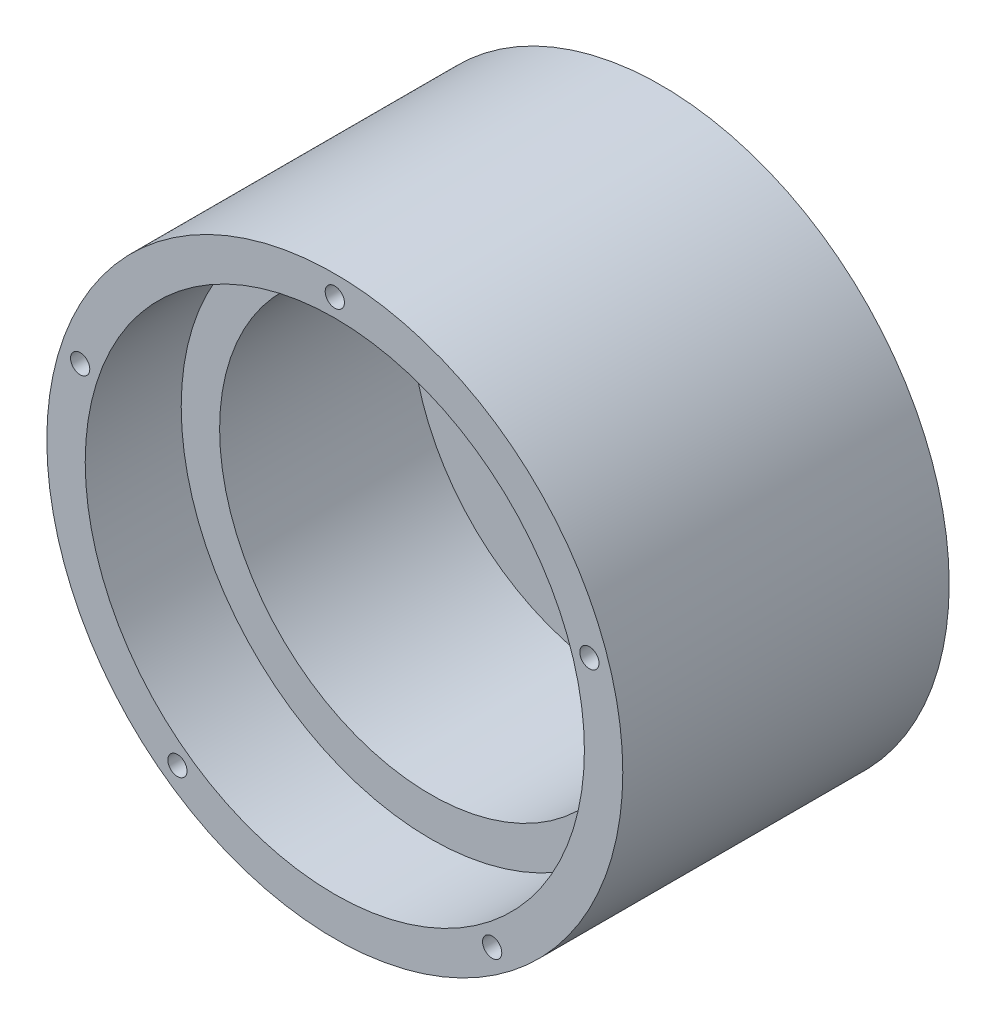
SolidWorks part; units mm, degrees
ref_plane "Front Plane" through (0, 0, 0) normal (1, 0, 0) x (0, 1, 0)
ref_plane "Top Plane" through (0, 0, 0) normal (0, 0, 1) x (0, 1, 0)
ref_plane "Right Plane" through (0, 0, 0) normal (0, 1, 0) x (-1, 0, 0)
sketch "Sketch2" plane through (0, 0, 0) normal (0, 0, 1) x (0, 1, 0)
  circle A0 centre (0, 0) radius 75
  dimension "D1" = 150
extrude "Boss-Extrude1" add sketch "Sketch2" along normal blind 85 contours A0
sketch "Sketch4" plane through (0, 0, 85) normal (0, 0, 1) x (1, 0, 0)
  circle A0 centre (0, 0) radius 65
  dimension "D1" = 130
extrude "Cut-Extrude2" cut sketch "Sketch4" against normal blind 25
sketch "Sketch5" plane through (0, 0, 60) normal (0, 0, 1) x (1, 0, 0)
  circle A0 centre (0, 0) radius 55
  dimension "D1" = 110
extrude "Cut-Extrude3" cut sketch "Sketch5" against normal blind 50
sketch "Sketch7" plane through (0, 0, 85) normal (0, 0, 1) x (1, 0, 0)
  circle A0 centre (0, 69.7234) radius 2.5
  dimension "D1" = 5
extrude "Cut-Extrude4" cut sketch "Sketch7" against normal blind 20
pattern_circular "CirPattern1" count 5 over 360 about axis through (0, 0, 0) along (0, 0, 1) of "Cut-Extrude4"
sketch "Sketch8" plane through (0, 0, 0) normal (0, 0, -1) x (1, 0, 0)
  circle A0 centre (0, 70) radius 2.5
  circle A1 centre (0, 0) radius 75 construction
  point P2 (0, 69.9008)
  point P5 (0, 0)
  dimension "D1" = 70
extrude "Cut-Extrude5" cut sketch "Sketch8" against normal blind 10
pattern_circular "CirPattern2" count 4 over 360 about axis through (0, 0.0779, 0) along (0, 0, 1) of "Cut-Extrude5"
